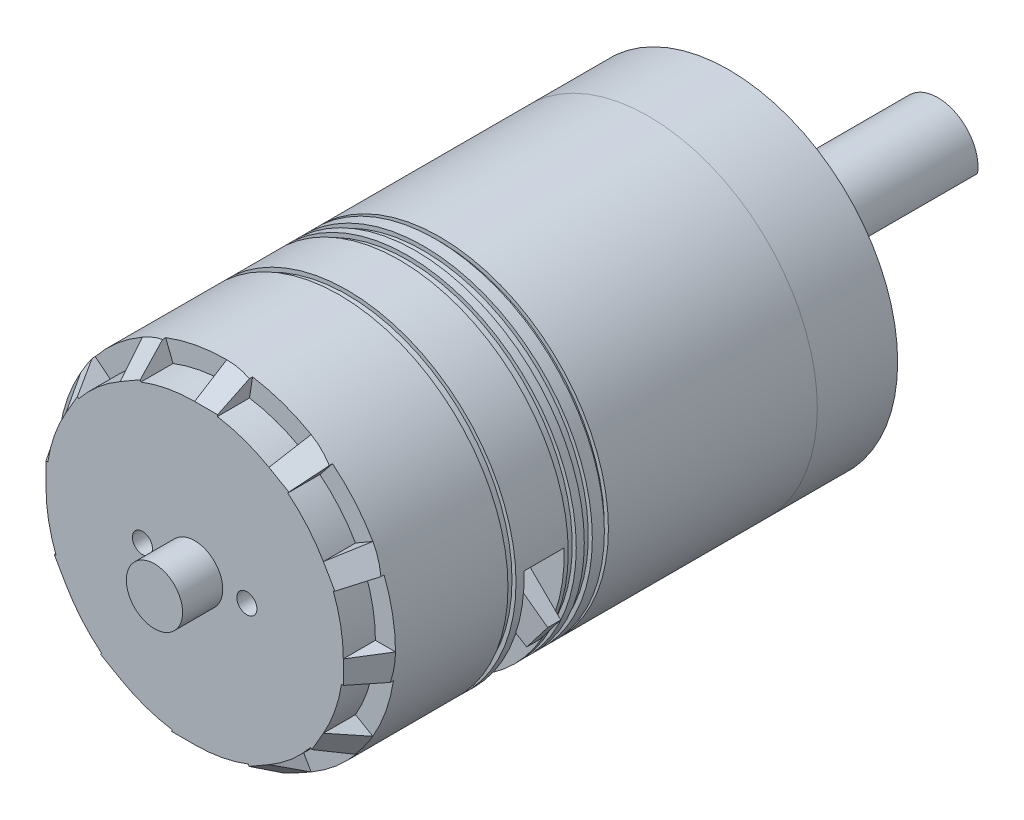
SolidWorks part; units mm, degrees
ref_plane "前视基准面" through (0, 0, 0) normal (0, 0, 1) x (1, 0, 0)
ref_plane "上视基准面" through (0, 0, 0) normal (0, 1, 0) x (1, 0, 0)
ref_plane "右视基准面" through (0, 0, 0) normal (1, 0, 0) x (0, 0, -1)
sketch "草图1" plane through (0, 0, 0) normal (0, 0, 1) x (1, 0, 0)
  circle A0 centre (0, 0) radius 21
  dimension "D1" = 42
extrude "凸台-拉伸1" add sketch "草图1" along normal blind 66.5
sketch "草图2" plane through (0, 0, 0) normal (0, 0, -1) x (-1, 0, 0)
  circle A0 centre (0, 0) radius 13
  dimension "D1" = 26
extrude "凸台-拉伸2" add sketch "草图2" along normal blind 2
sketch "草图3" plane through (0, 0, -2) normal (0, 0, -1) x (-1, 0, 0)
  circle A0 centre (0, 0) radius 5
  dimension "D1" = 10
extrude "凸台-拉伸3" add sketch "草图3" along normal blind 24
sketch "草图4" plane through (0, 0, -26) normal (0, 0, -1) x (-1, 0, 0)
  line L0 (-0.7071, -4.9497) -> (-4.9497, -0.7071)
  line L1 (0, 0) -> (0, -5) construction
  circle A0 centre (0, 0) radius 5 construction
  circle A1 centre (0, 0) radius 5 construction
  dimension "D1" = 4
  dimension "D2" = 45
extrude "切除-拉伸1" cut sketch "草图4" against normal blind 19.5 and the other way through all
hole_wizard "#8-36 螺纹孔1" positions "草图11" profile "草图12" tap size "#8-36" standard "ANSI Inch"
sketch "草图11" plane through (0, 0, 0) normal (0, 0, -1) x (-1, 0, 0)
  line L0 (0, 17.5) -> (0, 0) construction
  point P0 (0, 17.5)
  dimension "D1" = 17.5
sketch "草图12" plane through (0, 17.5, 0) normal (1, 0, 0) x (0, 1, 0)
  line L0 (0, 0) -> (0, 11.6517)
  line L1 (0, 11.6517) -> (2, 10.45)
  line L2 (2, 10.45) -> (2, 0)
  line L5 (2, 0) -> (0, 0)
  line L10 (0, 11.6517) -> (-2, 10.45) construction
  line L11 (0, -6.35) -> (0, 107.95) construction
  dimension "螺纹孔钻头直径" = 4
  dimension "螺纹孔钻头深度" = 10.45
  dimension "导头角度" = 118
cosmetic thread "孔螺蚊线1" parameters "D1"=8.33, "D2"=4.1656
chamfer "倒角1" distance 0.5 angle 45 1 edges at (-2, 17.5, 0)
pattern_circular "阵列(圆周)1" count 4 over 360 about axis through (0, 0, 0) along (0, 0, 1) of "#8-36 螺纹孔1", "倒角1"
sketch "草图13" plane through (0, 0, 0) normal (0, 0, -1) x (-1, 0, 0)
  line L0 (0, 21) -> (0, -21) construction
  line L1 (21, 0) -> (-21, 0) construction
  line L2 (0, 0) -> (14.8492, -14.8492) construction
  circle A0 centre (0, 0) radius 21 construction
  circle A1 centre (12.3744, -12.3744) radius 3
  circle A2 centre (12.3744, 12.3744) radius 3
  circle A3 centre (-12.3744, -12.3744) radius 3
  circle A4 centre (-12.3744, 12.3744) radius 3
  dimension "D1" = 45
  dimension "D2" = 17.5
  dimension "D3" = 6
sketch "草图30" plane through (0, 0, 66.5) normal (0, 0, 1) x (1, 0, 0)
  circle A0 centre (0, 0) radius 3.5
  dimension "D1" = 7
extrude "凸台-拉伸4" add sketch "草图30" along normal blind 5
sketch "草图31" plane through (0, 0, -2) normal (0, 0, -1) x (-1, 0, 0)
  circle A0 centre (0, 0) radius 8.25
  dimension "D1" = 16.5
extrude "凸台-拉伸5" add sketch "草图31" along normal blind 1
sketch "草图34" plane through (0, 0, 0) normal (0, 0, -1) x (-1, 0, 0)
  circle A0 centre (0, 0) radius 21
sketch3d "3D草图5"
  line L0 (0, 0, 0) -> (0, 0, 67.985)
  line L1 (21.6986, 0, 41.5) -> (15.6924, 6.0062, 41.5)
  line L3 (0, -21.6986, 41.5) -> (-6.0062, -15.6924, 41.5)
  line L4 (0, 0, -1.515) -> (0, 0, -26)
  line L5 (-6.0062, -15.6924, 41.5) -> (15.6924, 6.0062, 41.5)
  circle A1 centre (0, 0, 0) radius 21 construction
  arc A2 (0.7071, -4.9497, -26) -> (4.9497, -0.7071, -26) centre (0, 0, -26) ccw construction
  arc A5 (0, -21.6986, 41.5) -> (21.6986, 0, 41.5) centre (0, 0, 41.5) cw
  point P7 (0, 0, 21)
  point P15 (0, 0, -31)
  point P19 (0, 0, 63.1986)
  dimension "D2" = 41.5
  dimension "D1" = 41.5
extrude "切除-拉伸4" cut sketch "3D草图5" along a picked direction on the side against the normal blind 5 contours A5 L1 L5 L3
ref_plane "基准面1" through (0, 0, 48.5) normal (0, 0, 1) x (1, 0, 0)
sketch "草图38" plane through (0, 0, 48.5) normal (0, 0, 1) x (1, 0, 0)
  circle A0 centre (0, 0) radius 21 construction
  circle A1 centre (0, 0) radius 20.5
  circle A2 centre (0, 0) radius 21
  dimension "D1" = 41
extrude "切除-拉伸8" cut sketch "草图38" against normal blind 1
sketch "草图35" plane through (0, 0, 46.5) normal (0, 0, -1) x (-1, 0, 0)
  line L0 (-19.6508, 0.7225) -> (-13.5583, -7.2165)
  line L2 (-13.5583, -7.2165) -> (-10.385, -4.7813)
  line L3 (-10.385, -4.7813) -> (-16.6046, 3.3233)
  line L4 (-16.6046, 3.3233) -> (-19.6508, 0.9856)
  line L5 (-19.6508, 0.9856) -> (-19.6508, 0.7225)
extrude "凸台-拉伸8" add sketch "草图35" along normal blind 5
sketch "草图36" plane through (0, 0, 46.5) normal (0, 0, -1) x (-1, 0, 0)
  line L0 (0, -18.9231) -> (-7.5875, -12.4092)
  line L1 (-7.5875, -12.4092) -> (-4.982, -9.3742)
  line L2 (-4.982, -9.3742) -> (2.6055, -15.8881)
  line L3 (2.6055, -15.8881) -> (0, -18.9231)
extrude "凸台-拉伸9" add sketch "草图36" along normal blind 5
sketch "草图37" plane through (12.0185, -9.2231, 0) normal (0.7933, -0.6088, 0) x (0, 0, -1)
  line L0 (-41.5, 12.5367) -> (-46.5, 12.5367) construction
  line L1 (-43.367, 10.1324) -> (-45.6261, 10.1324)
  line L2 (-43.367, 10.1324) -> (-43.367, 5.2258)
  line L3 (-43.367, 5.2258) -> (-45.6261, 5.2258)
  line L4 (-45.6261, 10.1324) -> (-45.6261, 5.2258)
  line L5 (-46.5, 12.5367) -> (-46.5, 2.5293) construction
  dimension "D1" = 2.259
  dimension "D2" = 4.9065
  dimension "D3" = 2.4043
  dimension "D4" = 0.8739
extrude "凸台-拉伸10" add sketch "草图37" along normal blind 6 draft 3
ref_plane "基准面2" through (0, 0, 36) normal (0, 0, -1) x (-1, 0, 0)
sketch "草图39" plane through (0, 0, 36) normal (0, 0, -1) x (-1, 0, 0)
  circle A0 centre (0, 0) radius 21
  circle A1 centre (0, 0) radius 20.5
  dimension "D1" = 41
  dimension "D2" = 0.5
extrude "切除-拉伸9" cut sketch "草图39" against normal blind 0.5
ref_plane "基准面3" through (0, 0, 38) normal (0, 0, -1) x (-1, 0, 0)
sketch "草图41" plane through (0, 0, 38) normal (0, 0, -1) x (-1, 0, 0)
  circle A0 centre (0, 0) radius 21
  circle A1 centre (0, 0) radius 20.5
  dimension "D1" = 41
  dimension "D2" = 42
extrude "切除-拉伸10" cut sketch "草图41" against normal blind 1
ref_plane "基准面4" through (0, 0, 40) normal (0, 0, -1) x (-1, 0, 0)
sketch "草图42" plane through (0, 0, 40) normal (0, 0, -1) x (-1, 0, 0)
  circle A0 centre (0, 0) radius 21
  circle A1 centre (0, 0) radius 20.5
  dimension "D1" = 41
  dimension "D2" = 42
extrude "切除-拉伸11" cut sketch "草图42" against normal blind 1
ref_plane "基准面5" through (0, 0, 62.5) normal (0, 0, 1) x (1, 0, 0)
sketch "草图43" plane through (0, 0, 62.5) normal (0, 0, 1) x (1, 0, 0)
  line L0 (0, 18.5) -> (0, 21)
  line L1 (0, 0) -> (-10.5, 18.1865) construction
  line L2 (-6.6932, 17.2468) -> (-7.5977, 19.5774)
  arc A0 (0, 21) -> (-7.5977, 19.5774) centre (0, 0) ccw
  arc A1 (0, 18.5) -> (-6.6932, 17.2468) centre (0, 0) ccw
  dimension "D1" = 30
  dimension "D2" = 21
  dimension "D3" = 37
  dimension "D4" = 8.79
extrude "切除-拉伸12" cut sketch "草图43" along normal up to next
pattern_circular "阵列(圆周)4" count 12 over 360 about axis through (0, 0, 0) along (0, 0, 1) of "切除-拉伸12"
ref_plane "基准面6" through (0, 0, 0) normal (-0.866, -0.5, 0) x (0, 0, 1)
sketch "草图45" plane through (0, 0, 0) normal (-0.866, -0.5, 0) x (0, 0, 1)
  line L0 (62.5, 21) -> (66.5, 18.5)
  line L1 (66.5, 18.5) -> (66.5, 21)
  line L2 (66.5, 21) -> (62.5, 21)
extrude "切除-拉伸13" cut sketch "草图45" against normal up to next
pattern_circular "阵列(圆周)5" count 12 over 360 about axis through (0, 0, 0) along (0, 0, 1) of "切除-拉伸13"
sketch "草图48" plane through (0, 0, 0) normal (0, 1, 0) x (1, 0, 0)
  line L0 (21, -10) -> (-21, -10)
  line L1 (21, -36) -> (21, 0) construction
  line L2 (-21, 0) -> (-21, -36) construction
  line L3 (21, 0) -> (-21, 0) construction
  dimension "D1" = 10
split line "分割线2"
hole_wizard "M3 螺纹孔1" positions "草图50" profile "草图49" tap size "M3" standard "GB"
sketch "草图50" plane through (0, 0, 66.5) normal (0, 0, 1) x (1, 0, 0)
  line L0 (-6.5, 0) -> (0, 0) construction
  line L1 (0, 0) -> (0, 3.5) construction
  circle A0 centre (0, 0) radius 3.5 construction
  point P0 (-6.5, 0)
  point P14 (6.5, 0)
  dimension "D1" = 13
sketch "草图49" plane through (-6.5, 0, 66.5) normal (1, 0, 0) x (0, -1, 0)
  line L0 (0, 0) -> (0, 6.7511)
  line L1 (0, 6.7511) -> (1.25, 6)
  line L2 (1.25, 6) -> (1.25, 0)
  line L5 (1.25, 0) -> (0, 0)
  line L10 (0, 6.7511) -> (-1.25, 6) construction
  line L11 (0, -6.35) -> (0, 107.95) construction
  dimension "螺纹孔钻头直径" = 2.5
  dimension "螺纹孔钻头深度" = 6
  dimension "导头角度" = 118
cosmetic thread "孔螺蚊线2" parameters "D1"=4, "D2"=3
cosmetic thread "孔螺蚊线3" parameters "D1"=4, "D2"=3
extrude "切除-拉伸14" cut sketch "草图13" against normal blind 3
sketch "草图52" plane through (0, 0, 3) normal (0, 0, -1) x (-1, 0, 0)
  line L0 (0, 21) -> (0, 0) construction
  line L1 (13.8177, 12.3744) -> (13.0961, 13.6244)
  line L2 (13.0961, 13.6244) -> (11.6527, 13.6244)
  line L3 (11.6527, 13.6244) -> (10.931, 12.3744)
  line L4 (10.931, 12.3744) -> (11.6527, 11.1244)
  line L5 (11.6527, 11.1244) -> (13.0961, 11.1244)
  line L6 (13.0961, 11.1244) -> (13.8177, 12.3744)
  line L7 (0, 0) -> (-21, 0) construction
  line L8 (-13.0961, 11.1244) -> (-13.8177, 12.3744)
  line L9 (-11.6527, 11.1244) -> (-13.0961, 11.1244)
  line L10 (-10.931, 12.3744) -> (-11.6527, 11.1244)
  line L11 (-11.6527, 13.6244) -> (-10.931, 12.3744)
  line L12 (-13.0961, 13.6244) -> (-11.6527, 13.6244)
  line L13 (-13.8177, 12.3744) -> (-13.0961, 13.6244)
  line L14 (-13.8177, -12.3744) -> (-13.0961, -13.6244)
  line L15 (-13.0961, -13.6244) -> (-11.6527, -13.6244)
  line L16 (-11.6527, -13.6244) -> (-10.931, -12.3744)
  line L17 (-10.931, -12.3744) -> (-11.6527, -11.1244)
  line L18 (-11.6527, -11.1244) -> (-13.0961, -11.1244)
  line L19 (-13.0961, -11.1244) -> (-13.8177, -12.3744)
  line L20 (13.0961, -11.1244) -> (13.8177, -12.3744)
  line L21 (11.6527, -11.1244) -> (13.0961, -11.1244)
  line L22 (10.931, -12.3744) -> (11.6527, -11.1244)
  line L23 (11.6527, -13.6244) -> (10.931, -12.3744)
  line L24 (13.0961, -13.6244) -> (11.6527, -13.6244)
  line L25 (13.8177, -12.3744) -> (13.0961, -13.6244)
  circle A0 centre (12.3744, 12.3744) radius 1.25 construction
  circle A1 centre (-12.3744, 12.3744) radius 1.25 construction
  circle A2 centre (-12.3744, -12.3744) radius 1.25 construction
  circle A3 centre (12.3744, -12.3744) radius 1.25 construction
  dimension "D1" = 2.5
extrude "切除-拉伸15" cut sketch "草图52" against normal blind 1
sketch "草图53" plane through (0, 0, 0) normal (0, 0, -1) x (-1, 0, 0)
  circle A0 centre (0, 0) radius 17.5
move or copy body "实体-移动/复制1" [suppressed] bodies to move or copy 143
